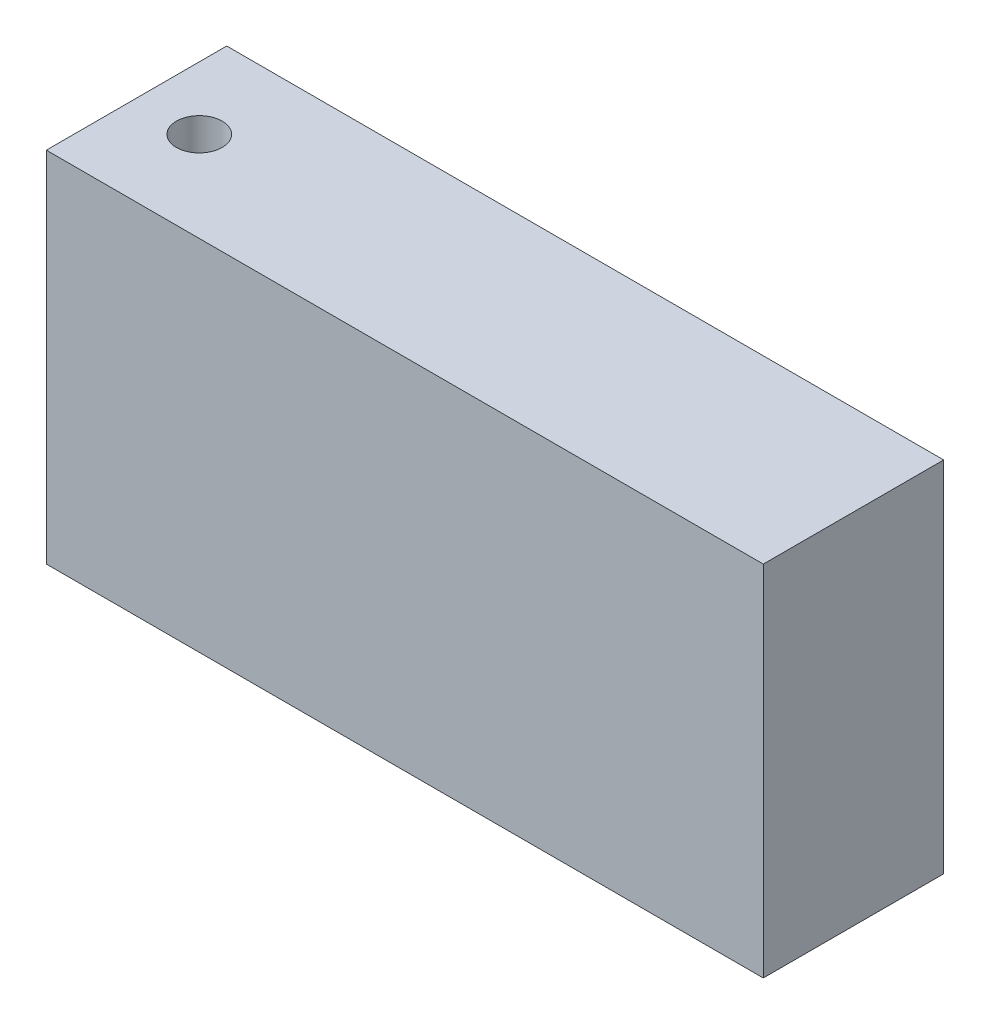
SolidWorks part; units mm, degrees
ref_plane "Front" through (0, 0, 0) normal (0, 0, 1) x (1, 0, 0)
ref_plane "Top" through (0, 0, 0) normal (0, 1, 0) x (1, 0, 0)
ref_plane "Right" through (0, 0, 0) normal (1, 0, 0) x (0, 0, -1)
sketch "Sketch1" plane through (0, 0, 0) normal (0, 1, 0) x (1, 0, 0)
  line L1 (50, -12.58) -> (-50, -12.58)
  line L2 (50, -12.58) -> (50, 12.58)
  line L3 (50, 12.58) -> (-50, 12.58)
  line L4 (-50, -12.58) -> (-50, 12.58)
  line L5 (50, -12.58) -> (-50, 12.58) construction
  line L6 (50, 12.58) -> (-50, -12.58) construction
  point P0 (0, 0)
  dimension "D1" = 100
  dimension "D2" = 25.16
extrude "Boss-Extrude1" add sketch "Sketch1" along normal blind 50
sketch "Sketch2" plane through (0, 50, 0) normal (0, 1, 0) x (1, 0, 0)
  line L0 (50, 12.58) -> (-50, 12.58) construction
  line L1 (-50, 12.58) -> (-50, -12.58) construction
  circle A0 centre (-41.25, 0) radius 3.19
  point P6 (0, 0)
  dimension "D3" = 6.38
  dimension "D1" = 12.58
  dimension "D2" = 8.75
extrude "Cut-Extrude1" cut sketch "Sketch2" against normal blind 8 contours A0
